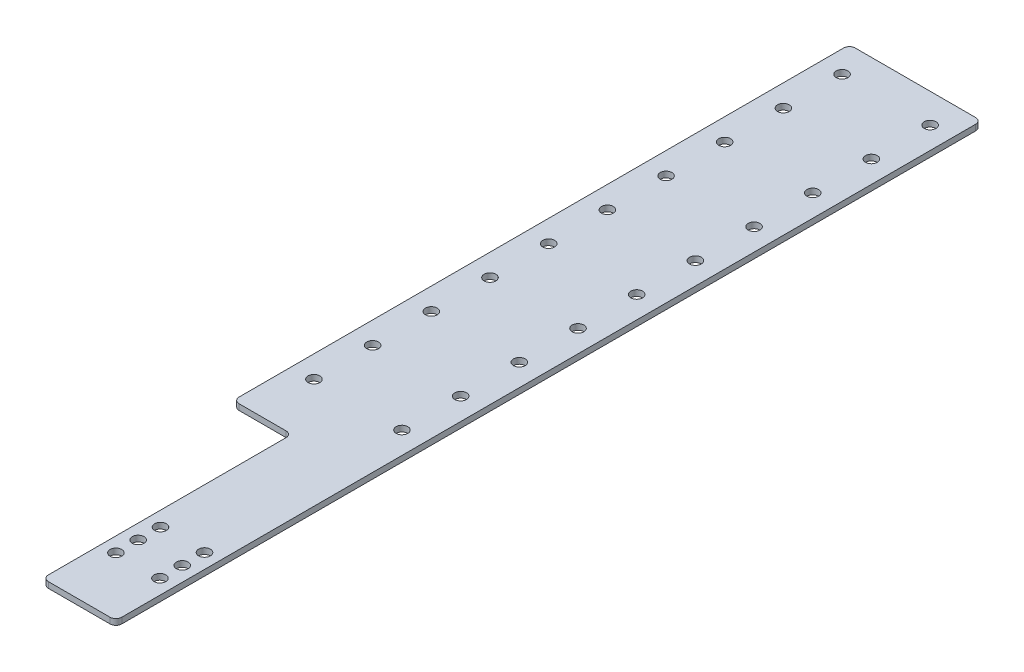
SolidWorks part; units mm, degrees
ref_plane "Front" through (0, 0, 0) normal (0, 0, 1) x (1, 0, 0)
ref_plane "Top" through (0, 0, 0) normal (0, 1, 0) x (1, 0, 0)
ref_plane "Right" through (0, 0, 0) normal (1, 0, 0) x (0, 0, -1)
sketch "Sketch1" plane through (0, 0, 0) normal (0, 1, 0) x (1, 0, 0)
  line L0 (-34.1884, -6.7119) -> (-2.4384, -6.7119)
  line L1 (-2.4384, -6.7119) -> (-2.4384, 367.9381)
  line L2 (-2.4384, 367.9381) -> (-59.5884, 367.9381)
  line L3 (-59.5884, 367.9381) -> (-59.5884, 101.2381)
  line L4 (-59.5884, 101.2381) -> (-34.1884, 101.2381)
  line L5 (-34.1884, 101.2381) -> (-34.1884, -6.7119)
  dimension "D1" = 374.65
  dimension "D2" = 107.95
  dimension "D3" = 31.75
  dimension "D4" = 25.4
extrude "Boss-Extrude1" add sketch "Sketch1" along normal mid plane 2.54 contours L0 L1 L2 L3 L4 L5
sketch "Sketch2" plane through (0, 1.27, 0) normal (0, 1, 0) x (1, 0, 0)
  line L0 (-34.1884, -6.7119) -> (-2.4384, -6.7119) construction
  line L1 (-34.1884, 101.2381) -> (-34.1884, -6.7119) construction
  circle A0 centre (-27.8384, 18.6881) radius 2.54
  circle A1 centre (-8.7884, 18.6881) radius 2.54
  circle A2 centre (-8.7884, 28.3401) radius 2.54
  circle A3 centre (-8.7884, 37.9921) radius 2.54
  circle A4 centre (-27.8384, 28.3401) radius 2.54
  circle A5 centre (-27.8384, 37.9921) radius 2.54
  dimension "D5" = 5.08
  dimension "D1" = 25.4
  dimension "D2" = 6.35
  dimension "D3" = 2
  dimension "D4" = 3
extrude "Cut-Extrude1" cut sketch "Sketch2" against normal through all both and the other way through all
sketch "Sketch3" plane through (0, 1.27, 0) normal (0, 1, 0) x (1, 0, 0)
  line L0 (-59.5884, 101.2381) -> (-34.1884, 101.2381) construction
  line L1 (-59.5884, 367.9381) -> (-59.5884, 101.2381) construction
  circle A0 centre (-50.0634, 126.6381) radius 2.54
  circle A1 centre (-11.9634, 126.6381) radius 2.54
  circle A2 centre (-11.9634, 152.0381) radius 2.54
  circle A3 centre (-11.9634, 177.4381) radius 2.54
  circle A4 centre (-11.9634, 202.8381) radius 2.54
  circle A5 centre (-11.9634, 228.2381) radius 2.54
  circle A6 centre (-11.9634, 253.6381) radius 2.54
  circle A7 centre (-11.9634, 279.0381) radius 2.54
  circle A8 centre (-11.9634, 304.4381) radius 2.54
  circle A9 centre (-11.9634, 329.8381) radius 2.54
  circle A10 centre (-11.9634, 355.2381) radius 2.54
  circle A11 centre (-50.0634, 152.0381) radius 2.54
  circle A12 centre (-50.0634, 177.4381) radius 2.54
  circle A13 centre (-50.0634, 202.8381) radius 2.54
  circle A14 centre (-50.0634, 228.2381) radius 2.54
  circle A15 centre (-50.0634, 253.6381) radius 2.54
  circle A16 centre (-50.0634, 279.0381) radius 2.54
  circle A17 centre (-50.0634, 304.4381) radius 2.54
  circle A18 centre (-50.0634, 329.8381) radius 2.54
  circle A19 centre (-50.0634, 355.2381) radius 2.54
  dimension "D1" = 5.08
  dimension "D2" = 25.4
  dimension "D3" = 9.525
  dimension "D4" = 2
  dimension "D5" = 10
extrude "Cut-Extrude2" cut sketch "Sketch3" against normal through all both and the other way through all
fillet "Fillet2" radius 2.54 6 edges at (-59.5884, 0, -367.9381) (-2.4384, 0, -367.9381) (-2.4384, 0, 6.7119) (-34.1884, 0, 6.7119) (-59.5884, 0, -101.2381) (-34.1884, 0, -101.2381)
